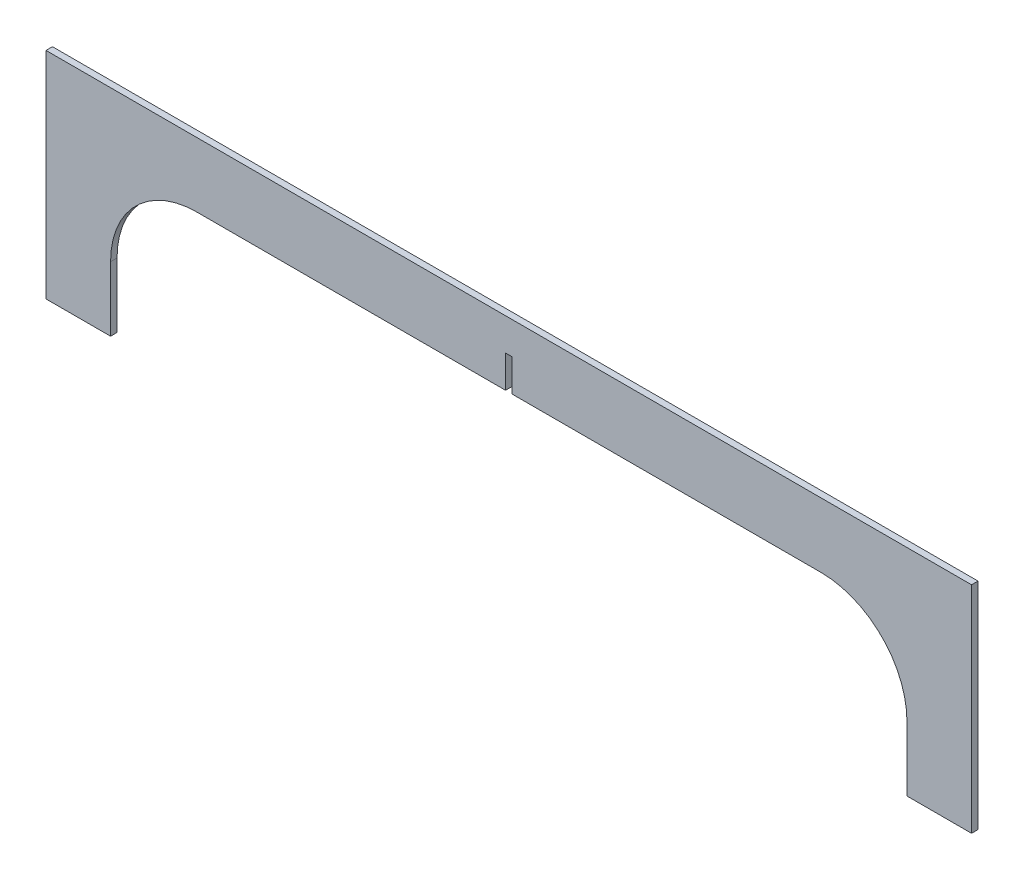
SolidWorks part; units mm, degrees
ref_plane "Front Plane" through (0, 0, 0) normal (0, 0, 1) x (1, 0, 0)
ref_plane "Top Plane" through (0, 0, 0) normal (0, 1, 0) x (1, 0, 0)
ref_plane "Right Plane" through (0, 0, 0) normal (1, 0, 0) x (0, 0, -1)
sketch "Sketch1" plane through (0, 0, 0) normal (0, 0, 1) x (1, 0, 0)
  line L0 (0, 0) -> (0, 100)
  line L1 (0, 100) -> (430, 100)
  line L2 (430, 100) -> (430, 0)
  line L3 (430, 0) -> (400, 0)
  line L4 (400, 0) -> (400, 70)
  line L5 (30, 70) -> (213.5, 70)
  line L6 (30, 70) -> (30, 0)
  line L7 (30, 0) -> (0, 0)
  line L8 (213.5, 70) -> (213.5, 85)
  line L9 (213.5, 85) -> (216.5, 85)
  line L10 (216.5, 85) -> (216.5, 70)
  line L11 (216.5, 70) -> (400, 70)
  dimension "D1" = 430
  dimension "D2" = 100
  dimension "D5" = 30
  dimension "D4" = 30
  dimension "D6" = 30
  dimension "D7" = 15
  dimension "D8" = 3
  dimension "D3" = 30
  dimension "D9" = 370
  dimension "D10" = 183.5
  dimension "D11" = 183.5
extrude "Boss-Extrude1" add sketch "Sketch1" along normal blind 3
fillet "Fillet1" radius 40 2 edges at (400, 70, 1.5) (30, 70, 1.5)
equation "\"D10@Sketch1\"=(\"D9@Sketch1\"-\"D8@Sketch1\")/2"
